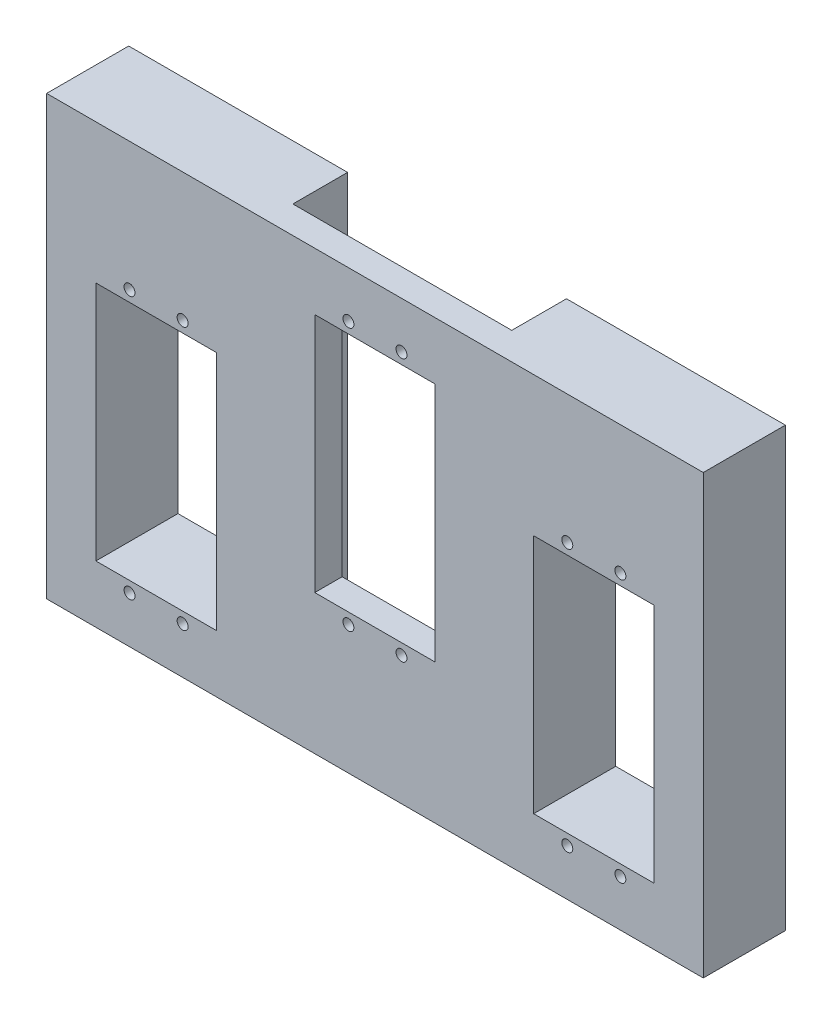
SolidWorks part; units mm, degrees
material "Polylactic Acid"
ref_plane "Top Plane" through (0, 0, 0) normal (0, 0, 1) x (1, 0, 0)
ref_plane "Right Plane" through (0, 0, 0) normal (0, 1, 0) x (1, 0, 0)
ref_plane "Front Plane" through (0, 0, 0) normal (1, 0, 0) x (0, 0, -1)
sketch "Sketch1" plane through (0, 0, 0) normal (0, 0, 1) x (1, 0, 0)
  line L1 (60, -40) -> (-60, -40)
  line L2 (60, -40) -> (60, 40)
  line L3 (60, 40) -> (-60, 40)
  line L4 (-60, -40) -> (-60, 40)
  line L5 (60, -40) -> (-60, 40) construction
  line L6 (60, 40) -> (-60, -40) construction
  point P0 (0, 0)
  dimension "D1" = 80
  dimension "D2" = 120
extrude "Boss-Extrude1" add sketch "Sketch1" along normal mid plane 15
sketch "Sketch2" plane through (0, 0, 7.5) normal (0, 0, 1) x (1, 0, 0)
  line L0 (-44.85, -31.5) -> (-35.15, -31.5) construction
  line L1 (-51, -29.5) -> (-29, -29.5)
  line L2 (-51, -29.5) -> (-51, 14.5)
  line L3 (-51, 14.5) -> (-29, 14.5)
  line L4 (-29, -29.5) -> (-29, 14.5)
  line L5 (-51, -29.5) -> (-29, 14.5) construction
  line L6 (-51, 14.5) -> (-29, -29.5) construction
  line L7 (-44.85, -31.5) -> (-44.85, 16.5) construction
  line L8 (-60, -40) -> (60, -40) construction
  line L14 (-40, -7.5) -> (0, -7.5) construction
  line L15 (-40, -7.5) -> (-40, 7.5) construction
  line L16 (60, 40) -> (-60, 40) construction
  line L18 (29, -29.5) -> (51, -29.5)
  line L19 (29, -29.5) -> (29, 14.5)
  line L20 (29, 14.5) -> (51, 14.5)
  line L21 (51, -29.5) -> (51, 14.5)
  line L22 (35.15, -31.5) -> (44.85, -31.5) construction
  line L23 (29, -29.5) -> (51, 14.5) construction
  line L24 (29, 14.5) -> (51, -29.5) construction
  line L25 (35.15, -31.5) -> (35.15, 16.5) construction
  line L26 (-40, -7.5) -> (0, -7.5) construction
  line L35 (-11, -14.5) -> (11, -14.5)
  line L36 (-11, -14.5) -> (-11, 29.5)
  line L37 (-11, 29.5) -> (11, 29.5)
  line L38 (11, -14.5) -> (11, 29.5)
  line L39 (-4.85, -16.5) -> (4.85, -16.5) construction
  line L40 (-11, -14.5) -> (11, 29.5) construction
  line L41 (-11, 29.5) -> (11, -14.5) construction
  line L42 (-4.85, -16.5) -> (-4.85, 31.5) construction
  line L51 (35.15, -16.5) -> (35.15, 31.5) construction
  line L52 (-11, -29.5) -> (11, -29.5) [skipped]
  line L53 (-11, -29.5) -> (-11, 14.5) [skipped]
  line L54 (-11, 14.5) -> (11, 14.5) [skipped]
  line L55 (11, -29.5) -> (11, 14.5) [skipped]
  line L56 (-4.85, -31.5) -> (4.85, -31.5) construction
  line L57 (-11, -29.5) -> (11, 14.5) construction
  line L58 (-11, 14.5) -> (11, -29.5) construction
  line L59 (-4.85, -31.5) -> (-4.85, 16.5) construction
  line L60 (29, -14.5) -> (51, -14.5) [skipped]
  line L61 (29, -14.5) -> (29, 29.5) [skipped]
  line L62 (29, 29.5) -> (51, 29.5) [skipped]
  line L63 (51, -14.5) -> (51, 29.5) [skipped]
  line L64 (35.15, -16.5) -> (44.85, -16.5) construction
  line L65 (29, -14.5) -> (51, 29.5) construction
  line L66 (29, 29.5) -> (51, -14.5) construction
  line L67 (-44.85, -16.5) -> (-44.85, 31.5) construction
  line L68 (-51, -14.5) -> (-29, -14.5) [skipped]
  line L69 (-51, -14.5) -> (-51, 29.5) [skipped]
  line L70 (-51, 29.5) -> (-29, 29.5) [skipped]
  line L71 (-29, -14.5) -> (-29, 29.5) [skipped]
  line L72 (-44.85, -16.5) -> (-35.15, -16.5) construction
  line L73 (-51, -14.5) -> (-29, 29.5) construction
  line L74 (-51, 29.5) -> (-29, -14.5) construction
  circle A0 centre (-44.85, -31.5) radius 1
  circle A1 centre (-35.15, -31.5) radius 1
  circle A2 centre (-35.15, 16.5) radius 1
  circle A3 centre (-44.85, 16.5) radius 1
  circle A44 centre (35.15, -31.5) radius 1
  circle A45 centre (44.85, -31.5) radius 1
  circle A46 centre (44.85, 16.5) radius 1
  circle A47 centre (35.15, 16.5) radius 1
  circle A52 centre (-4.85, -16.5) radius 1
  circle A53 centre (4.85, -16.5) radius 1
  circle A54 centre (4.85, 31.5) radius 1
  circle A55 centre (-4.85, 31.5) radius 1
  circle A60 centre (-4.85, -31.5) radius 1 [skipped]
  circle A61 centre (4.85, -31.5) radius 1 [skipped]
  circle A62 centre (4.85, 16.5) radius 1 [skipped]
  circle A63 centre (-4.85, 16.5) radius 1 [skipped]
  circle A64 centre (35.15, -16.5) radius 1 [skipped]
  circle A65 centre (44.85, -16.5) radius 1 [skipped]
  circle A66 centre (44.85, 31.5) radius 1 [skipped]
  circle A67 centre (35.15, 31.5) radius 1 [skipped]
  circle A68 centre (-44.85, -16.5) radius 1 [skipped]
  circle A69 centre (-35.15, -16.5) radius 1 [skipped]
  circle A70 centre (-35.15, 31.5) radius 1 [skipped]
  circle A71 centre (-44.85, 31.5) radius 1 [skipped]
  point P0 (-40, -7.5)
  point P8 (-44.85, -7.5)
  point P9 (-40, -31.5)
  point P18 (37.33, -7.5)
  point P22 (40, 7.5)
  point P23 (-40, 7.5)
  point P27 (0, 0)
  point P38 (40, -7.5)
  point P74 (0, 7.5)
  point P105 (0, -7.5)
  dimension "D7" = 2
  dimension "D11" = 40
  dimension "D3" = 9.7
  dimension "D4" = 48
  dimension "D5" = 44
  dimension "D6" = 22
  dimension "D8" = 32.5
  dimension "D10" = 3
  dimension "D13" = 2
  dimension "D9" = 40
  dimension "D12" = 32.5
  dimension "D1" = 2
  dimension "D2" = 2
extrude "Cut-Extrude1" cut sketch "Sketch2" against normal up to surface (15 mm away) up to face at (0, 0, -7.5)
sketch "Sketch3" plane through (0, 40, 0) normal (0, 1, 0) x (1, 0, 0)
  line L0 (60, 7.5) -> (-60, 7.5) construction
  line L1 (20, -2.5) -> (-20, -2.5)
  line L2 (20, -2.5) -> (20, 7.5)
  line L3 (20, 7.5) -> (-20, 7.5)
  line L4 (-20, -2.5) -> (-20, 7.5)
  line L5 (20, -2.5) -> (-20, 7.5) construction
  line L6 (20, 7.5) -> (-20, -2.5) construction
  line L7 (60, -7.5) -> (-60, -7.5) construction
  point P0 (0, 2.5)
  point P7 (0, 0)
  point P8 (0, 0)
  dimension "D1" = 40
  dimension "D2" = 5
extrude "Cut-Extrude2" cut sketch "Sketch3" against normal up to surface (80 mm away) up to face at (0, -40, 0)
